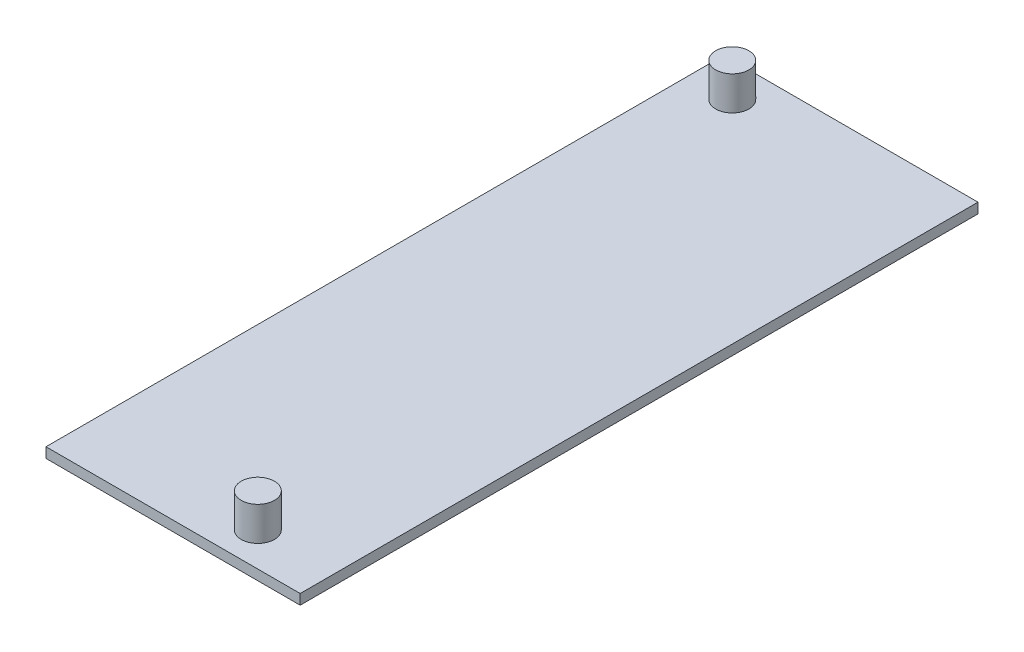
SolidWorks part; units mm, degrees
ref_plane "Front Plane" through (0, 0, 0) normal (0, 0, 1) x (1, 0, 0)
ref_plane "Top Plane" through (0, 0, 0) normal (0, 1, 0) x (1, 0, 0)
ref_plane "Right Plane" through (0, 0, 0) normal (1, 0, 0) x (0, 0, -1)
sketch "Sketch1" plane through (0, 0, 0) normal (0, 0, 1) x (1, 0, 0)
  line L1 (0, 0) -> (75, 0)
  line L2 (0, 0) -> (0, 3)
  line L3 (0, 3) -> (75, 3)
  line L4 (75, 0) -> (75, 3)
  dimension "D1" = 3
  dimension "D2" = 75
extrude "Boss-Extrude1" add sketch "Sketch1" along normal blind 200
sketch "Sketch2" plane through (0, 3, 0) normal (0, 1, 0) x (1, 0, 0)
  line L1 (75, 0) -> (-150, 0)
  line L2 (75, 0) -> (75, -200)
  line L3 (75, -200) -> (-150, -200)
  line L4 (-150, 0) -> (-150, -200)
  line L5 (62.5, -200) -> (-137.5, -200)
  line L6 (62.5, -200) -> (62.5, 0)
  line L7 (62.5, 0) -> (-137.5, 0)
  line L8 (-137.5, -200) -> (-137.5, 0)
  circle A0 centre (52.5, -190) radius 4.9
  circle A1 centre (12.5, -10) radius 4.9
  dimension "D4" = 10
  dimension "D5" = 10
  dimension "D6" = 9.8
  dimension "D7" = 9.8
  dimension "D8" = 10
  dimension "D9" = 40
  dimension "D1" = 225
  dimension "D2" = 12.5
  dimension "D3" = 12.5
extrude "Boss-Extrude2" add sketch "Sketch2" along normal blind 10 contours A1 | A0
sketch "Sketch3" plane through (0, 0, 0) normal (0, -1, 0) x (1, 0, 0)
  line L1 (25, 180) -> (30, 180)
  line L2 (25, 180) -> (25, 150)
  line L3 (25, 150) -> (30, 150)
  line L4 (30, 180) -> (30, 150)
  line L6 (25, 130) -> (30, 130)
  line L7 (25, 130) -> (25, 100)
  line L8 (25, 100) -> (30, 100)
  line L9 (30, 130) -> (30, 100)
  line L10 (25, 80) -> (30, 80)
  line L11 (25, 80) -> (25, 50)
  line L12 (25, 50) -> (30, 50)
  line L13 (30, 80) -> (30, 50)
  line L14 (25, 30) -> (30, 30)
  line L15 (25, 30) -> (25, 0)
  line L16 (25, 0) -> (30, 0)
  line L17 (30, 30) -> (30, 0)
  line L18 (0, 200) -> (75, 200) construction
  line L19 (75, 200) -> (75, 0) construction
  point P6 (27.5, 180)
  dimension "D1" = 47.5
  dimension "D2" = 5
  dimension "D3" = 30
  dimension "D5" = 20
  dimension "D4" = 4
extrude "Cut-Extrude1" cut sketch "Sketch3" against normal blind 1
